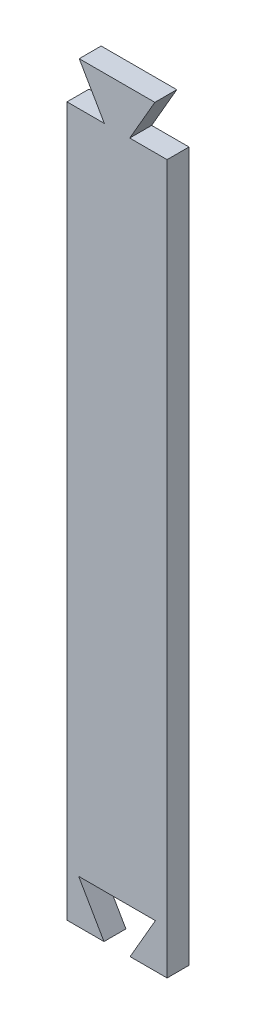
SolidWorks part; units mm, degrees
material "Custom Plastic"
ref_plane "X-Y Datum" through (0, 0, 0) normal (0, 0, 1) x (1, 0, 0)
ref_plane "X-Z Datum" through (0, 0, 0) normal (0, 1, 0) x (1, 0, 0)
ref_plane "Y-Z Datum" through (0, 0, 0) normal (1, 0, 0) x (0, 0, -1)
sketch "Sketch1" plane through (0, 0, 0) normal (0, 0, 1) x (1, 0, 0)
  line L0 (-3.0241, 0) -> (-8.89, 10.16)
  line L1 (-8.89, 10.16) -> (8.89, 10.16)
  line L2 (8.89, 10.16) -> (3.0241, 0)
  line L3 (3.0241, 0) -> (11.5976, 0)
  line L4 (11.5976, 0) -> (11.5976, 164.2364)
  line L5 (-3.0241, 0) -> (-11.5976, 0)
  line L6 (-11.5976, 0) -> (-11.5976, 164.2364)
  line L7 (-11.5976, 0) -> (11.5976, 0) construction
  line L8 (11.5976, 164.2364) -> (2.9411, 164.2364)
  line L9 (-11.5976, 82.1182) -> (11.5976, 82.1182) construction
  line L13 (-2.9411, 164.2364) -> (-11.5976, 164.2364)
  line L14 (-2.9411, 164.2364) -> (-8.763, 174.3202)
  line L15 (-8.763, 174.3202) -> (8.763, 174.3202)
  line L16 (8.763, 174.3202) -> (2.9411, 164.2364)
  line L17 (0, 174.3202) -> (0, 82.1182) construction
  point P7 (0, 0)
  point P9 (0, 10.16)
  dimension "D1" = 60
  dimension "D2" = 10.16
  dimension "D3" = 60
  dimension "D4" = 17.78
  dimension "D5" = 23.1952
  dimension "D6" = 164.2364
  dimension "D7" = 60
  dimension "D8" = 60
  dimension "D9" = 10.0838
  dimension "D10" = 17.526
extrude "Boss-Extrude1" add sketch "Sketch1" along normal blind 5.08
